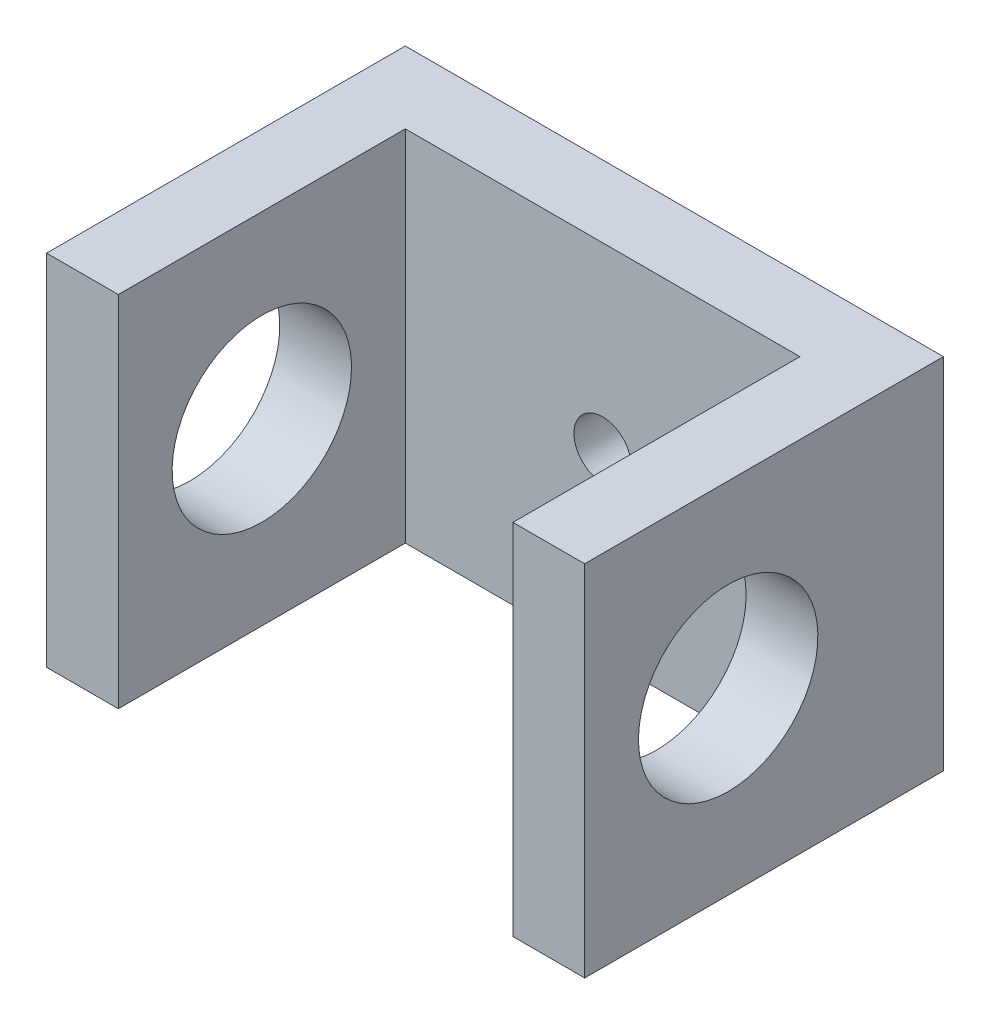
SolidWorks part; units mm, degrees
ref_plane "Front Plane" through (0, 0, 0) normal (0, 0, 1) x (1, 0, 0)
ref_plane "Top Plane" through (0, 0, 0) normal (0, 1, 0) x (1, 0, 0)
ref_plane "Right Plane" through (0, 0, 0) normal (1, 0, 0) x (0, 0, -1)
sketch "Sketch1" plane through (0, 0, 0) normal (0, 0, 1) x (1, 0, 0)
  line L1 (-7.5, 5) -> (7.5, 5)
  line L2 (-7.5, 5) -> (-7.5, -5)
  line L3 (-7.5, -5) -> (7.5, -5)
  line L4 (7.5, 5) -> (7.5, -5)
  line L5 (-7.5, 5) -> (7.5, -5) construction
  line L6 (-7.5, -5) -> (7.5, 5) construction
  point P0 (0, 0)
  dimension "D1" = 15
  dimension "D2" = 10
extrude "Boss-Extrude1" add sketch "Sketch1" along normal blind 2
sketch "Sketch2" plane through (0, 0, 2) normal (0, 0, 1) x (1, 0, 0)
  line L0 (7.5, 5) -> (-7.5, 5) construction
  line L1 (-7.5, -5) -> (-5.5, -5)
  line L2 (-7.5, -5) -> (-7.5, 5)
  line L3 (-7.5, 5) -> (-5.5, 5)
  line L4 (-5.5, -5) -> (-5.5, 5)
  line L6 (7.5, -5) -> (5.5, -5)
  line L7 (7.5, -5) -> (7.5, 5)
  line L8 (7.5, 5) -> (5.5, 5)
  line L9 (5.5, -5) -> (5.5, 5)
  dimension "D1" = 2
  dimension "D2" = 2
extrude "Boss-Extrude2" add sketch "Sketch2" along normal blind 8
sketch "Sketch3" plane through (-7.5, 0, 0) normal (-1, 0, 0) x (0, 0, 1)
  line L0 (0, 5) -> (0, -5) construction
  line L1 (10, -5) -> (0, -5) construction
  circle A0 centre (6, 0) radius 2.5
  dimension "D3" = 5
  dimension "D1" = 6
  dimension "D2" = 5
extrude "Cut-Extrude1" cut sketch "Sketch3" against normal through all
sketch "Sketch4" plane through (0, 0, 2) normal (0, 0, 1) x (1, 0, 0)
  circle A0 centre (0, 0) radius 0.8
extrude "Cut-Extrude2" cut sketch "Sketch4" against normal through all
